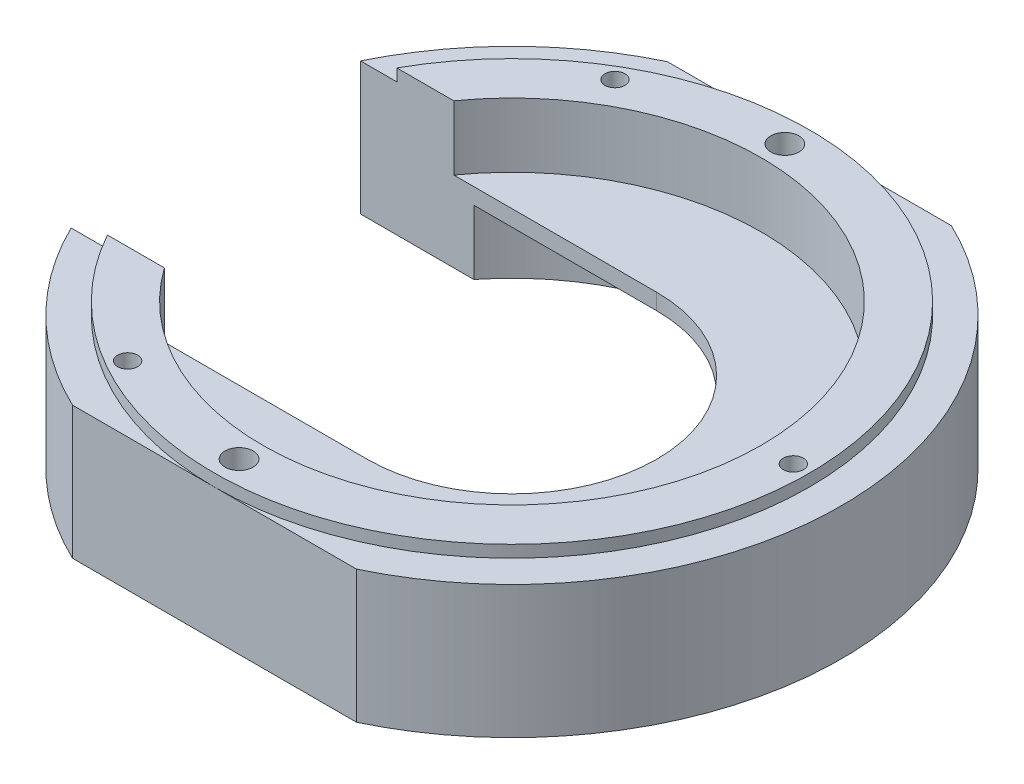
SolidWorks part; units mm, degrees
ref_plane "Front Plane" through (0, 0, 0) normal (0, 0, 1) x (1, 0, 0)
ref_plane "Top Plane" through (0, 0, 0) normal (0, 1, 0) x (1, 0, 0)
ref_plane "Right Plane" through (0, 0, 0) normal (1, 0, 0) x (0, 0, -1)
sketch "Sketch7" plane through (0, 0, 0) normal (0, 1, 0) x (1, 0, 0)
  line L1 (-50, -37) -> (50, -37)
  line L2 (-50, -37) -> (-50, 37)
  line L3 (-50, 37) -> (50, 37)
  line L4 (50, -37) -> (50, 37)
  line L5 (-50, -37) -> (50, 37) construction
  line L6 (-50, 37) -> (50, -37) construction
  line L7 (-36.8375, -18) -> (36.8375, -18)
  line L8 (-36.8375, -18) -> (-36.8375, 18)
  line L9 (-36.8375, 18) -> (36.8375, 18)
  line L10 (36.8375, -18) -> (36.8375, 18)
  line L11 (-36.8375, -18) -> (36.8375, 18) construction
  line L12 (-36.8375, 18) -> (36.8375, -18) construction
  circle A0 centre (0, 0) radius 41
  circle A1 centre (0, 0) radius 18
  dimension "D1" = 82
  dimension "D2" = 100
  dimension "D3" = 36
  dimension "74" = 74
extrude "Boss-Extrude3" add sketch "Sketch7" along normal blind 16.5 contours L9 A0 L3 | A1 L7 L10 L9 | L10 A0 | L1 A0 L7
sketch "Sketch11" plane through (0, 16.5, 0) normal (0, 1, 0) x (1, 0, 0)
  line L0 (0, 18) -> (-32.3265, 18)
  line L1 (-36.8375, 18) -> (0, 18) construction
  line L2 (-32.3265, -18) -> (0, -18)
  circle A0 centre (0, 0) radius 37
  circle A1 centre (0, 0) radius 18
  line M1 (-36.8375, 18) -> (0, 18)
  arc M2 (0, 18) -> (0, -18) centre (0, 0) cw
  line M3 (0, -18) -> (-36.8375, -18)
  dimension "D1" = 74
extrude "Boss-Extrude5" add sketch "Sketch11" along normal blind 1.5 contours A0 M1 M2 M3
sketch "Sketch13" plane through (0, 18, 0) normal (0, 1, 0) x (1, 0, 0)
  circle A0 centre (0, 0) radius 31
  dimension "D1" = 62
extrude "Cut-Extrude1" cut sketch "Sketch13" against normal blind 8
sketch "Sketch14" plane through (0, 0, 0) normal (0, -1, 0) x (1, 0, 0)
  circle A0 centre (0, 0) radius 29
  dimension "D1" = 58
extrude "Cut-Extrude2" cut sketch "Sketch14" against normal offset from surface (8 mm away) 2 up to face at (5.9403, 10, 0)
sketch "Sketch15" plane through (0, 0, 0) normal (0, -1, 0) x (1, 0, 0)
  line L0 (0, 0) -> (35, 0) construction
  line L1 (0, 0) -> (0, 33.95)
  dimension "D1" = 35
  dimension "D2" = 67.9
hole_wizard "M3 Tapped Hole1" positions "3DSketch2" profile "Sketch17" tap size "M3" standard "GB" end condition up to next
sketch3d "3DSketch2"
  point P0 (35, 0, 0)
sketch "Sketch17" plane through (35, 0, 0) normal (1, 0, 0) x (0, 0, -1)
  line L0 (0, 0) -> (0, 18)
  line L1 (0, 18) -> (1.25, 18)
  line L2 (1.25, 18) -> (1.25, 0)
  line L5 (1.25, 0) -> (0, 0)
  line L11 (0, -6.35) -> (0, 107.95) construction
  dimension "Thru Tap Drill Dia." = 2.5
  dimension "Thru Tap Drill Depth" = 18
cosmetic thread "Hole Thread1" parameters "D2"=3
pattern_circular "CirPattern1" count 3 over 360 about axis through (0, 0, 0) along (0, 1, 0) of "M3 Tapped Hole1"
cosmetic thread "Hole Thread2" parameters "D2"=3
cosmetic thread "Hole Thread3" parameters "D2"=3
hole_wizard "Hole1" positions "3DSketch4" profile "Sketch19" legacy end condition up to next
sketch3d "3DSketch4"
  point P0 (0, 0, 33.95)
  point P3 (-13.9122, 0, 3.3456)
sketch "Sketch19" plane through (0, 0, 33.95) normal (1, 0, 0) x (0, 0, -1)
  line L0 (0, 0) -> (0, 18)
  line L1 (0, 18) -> (1.75, 18)
  line L2 (1.75, 18) -> (1.75, 4)
  line L3 (1.75, 4) -> (3, 4)
  line L4 (3, 4) -> (3, 0)
  line L5 (3, 0) -> (0, 0)
  line L6 (0, -6.13) -> (0, 109.2824) construction
  line L7 (-1.75, 4) -> (-3, 4) construction
  line L8 (0, 18) -> (-1.75, 18) construction
  dimension "Diameter" = 3.5
  dimension "Depth" = 18
  dimension "C-Drill Diameter" = 6
  dimension "C-Drill Depth" = 4
  dimension "C-Drill Angle" = 180
pattern_circular "CirPattern2" count 2 over 360 about axis through (0, 0, 0) along (0, 1, 0) of "Hole1"
